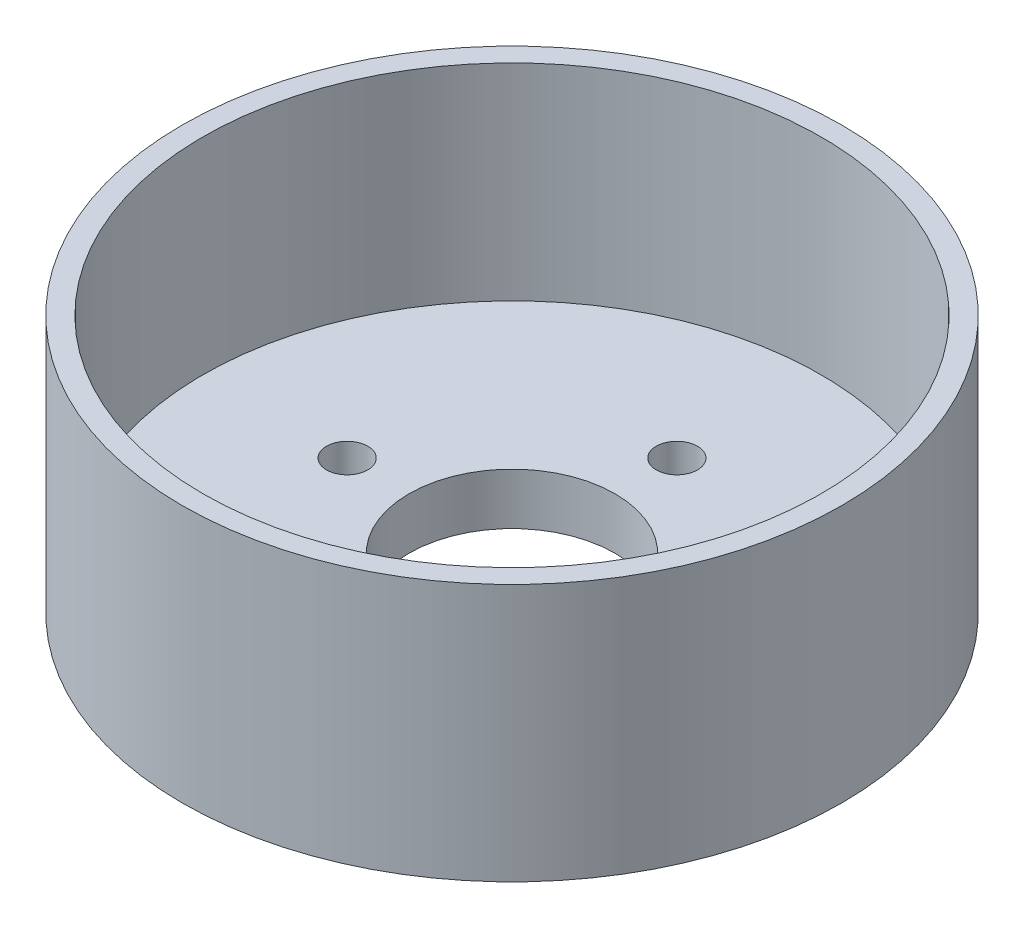
SolidWorks part; units mm, degrees
ref_plane "Front Plane" through (0, 0, 0) normal (0, 0, 1) x (1, 0, 0)
ref_plane "Top Plane" through (0, 0, 0) normal (0, 1, 0) x (1, 0, 0)
ref_plane "Right Plane" through (0, 0, 0) normal (1, 0, 0) x (0, 0, -1)
sketch "Sketch1" plane through (0, 0, 0) normal (0, 1, 0) x (1, 0, 0)
  circle A2 centre (0, 0) radius 16
extrude "Boss-Extrude1" add sketch "Sketch1" along normal blind 12.5
sketch "Sketch2" plane through (0, 12.5, 0) normal (0, 1, 0) x (1, 0, 0)
  circle A0 centre (0, 0) radius 15
extrude "Cut-Extrude1" cut sketch "Sketch2" against normal blind 10
sketch "Sketch3" plane through (0, 0, 0) normal (0, -1, 0) x (-1, 0, 0)
  circle A1 centre (0, 0) radius 5
extrude "Cut-Extrude2" cut sketch "Sketch3" against normal blind 10
sketch "Sketch4" plane through (0, 0, 0) normal (0, -1, 0) x (-1, 0, 0)
  circle A1 centre (0, 8) radius 1
  circle A2 centre (0, -8) radius 1
  circle A4 centre (-8, 0) radius 1
  circle A5 centre (8, 0) radius 1
extrude "Cut-Extrude3" cut sketch "Sketch4" against normal blind 10 contours A1 | A5 | A2 | A4
